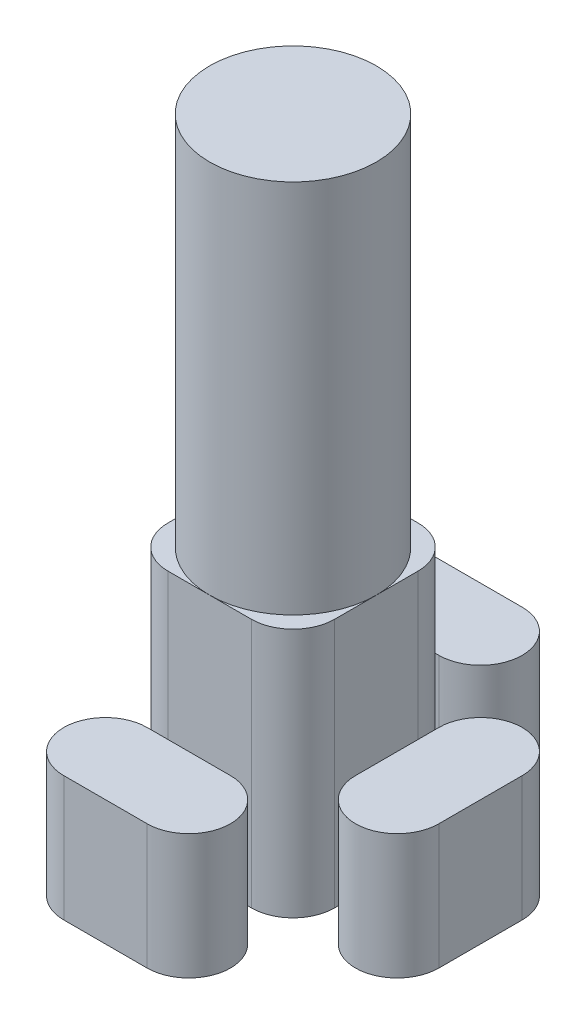
SolidWorks part; units mm, degrees
ref_plane "Front Plane" through (0, 0, 0) normal (0, 0, 1) x (1, 0, 0)
ref_plane "Top Plane" through (0, 0, 0) normal (0, 1, 0) x (1, 0, 0)
ref_plane "Right Plane" through (0, 0, 0) normal (1, 0, 0) x (0, 0, -1)
sketch "Sketch1" plane through (0, 0, 0) normal (0, 1, 0) x (1, 0, 0)
  line L0 (0, 0.2) -> (0, -0.2) construction
  line L1 (-0.1, -0.2) -> (0.1, -0.2)
  line L2 (-0.2, -0.1) -> (-0.2, 0.1)
  line L3 (-0.1, 0.2) -> (0.1, 0.2)
  line L4 (0.2, -0.1) -> (0.2, 0.1)
  line L5 (0.45, -0.1) -> (0.45, 0.1)
  line L6 (0.25, -0.1) -> (0.25, 0.1)
  line L11 (0.1, 0.25) -> (-0.1, 0.25)
  line L12 (0.1, 0.45) -> (-0.1, 0.45)
  line L13 (-0.2, 0) -> (0.2, 0) construction
  line L14 (0.1, -0.45) -> (-0.1, -0.45)
  line L15 (0.1, -0.25) -> (-0.1, -0.25)
  arc A1 (-0.2, 0.1) -> (-0.1, 0.2) centre (-0.1, 0.1) cw
  arc A2 (0.2, 0.1) -> (0.1, 0.2) centre (0.1, 0.1) ccw
  arc A3 (0.2, -0.1) -> (0.1, -0.2) centre (0.1, -0.1) cw
  arc A4 (-0.2, -0.1) -> (-0.1, -0.2) centre (-0.1, -0.1) ccw
  arc A5 (0.25, 0.1) -> (0.35, 0.2) centre (0.35, 0.1) cw
  arc A6 (0.45, 0.1) -> (0.35, 0.2) centre (0.35, 0.1) ccw
  arc A7 (0.45, -0.1) -> (0.35, -0.2) centre (0.35, -0.1) cw
  arc A8 (0.25, -0.1) -> (0.35, -0.2) centre (0.35, -0.1) ccw
  arc A17 (-0.1, 0.45) -> (-0.2, 0.35) centre (-0.1, 0.35) ccw
  arc A18 (0.1, 0.25) -> (0.2, 0.35) centre (0.1, 0.35) ccw
  arc A19 (0.1, 0.45) -> (0.2, 0.35) centre (0.1, 0.35) cw
  arc A20 (-0.1, 0.25) -> (-0.2, 0.35) centre (-0.1, 0.35) cw
  arc A21 (-0.1, -0.25) -> (-0.2, -0.35) centre (-0.1, -0.35) ccw
  arc A22 (0.1, -0.45) -> (0.2, -0.35) centre (0.1, -0.35) ccw
  arc A23 (0.1, -0.25) -> (0.2, -0.35) centre (0.1, -0.35) cw
  arc A24 (-0.1, -0.45) -> (-0.2, -0.35) centre (-0.1, -0.35) cw
  dimension "D1" = 0.05
  dimension "D2" = 2
extrude "Boss-Extrude1" add sketch "Sketch1" along normal blind 0.6
sketch "Sketch2" plane through (0, 0.6, 0) normal (0, 1, 0) x (1, 0, 0)
  line L0 (-0.1, -0.45) -> (0.1, -0.45) construction
  line L1 (0.1, -0.25) -> (-0.1, -0.25) construction
  line L2 (0.25, 0.1) -> (0.25, -0.1) construction
  line L3 (0.45, -0.1) -> (0.45, 0.1) construction
  line L4 (-0.1, 0.25) -> (0.1, 0.25) construction
  line L5 (0.1, 0.45) -> (-0.1, 0.45) construction
  line L6 (-0.1, -0.45) -> (0.1, -0.45)
  line L7 (0.1, -0.25) -> (-0.1, -0.25)
  line L8 (0.25, 0.1) -> (0.25, -0.1)
  line L9 (0.45, -0.1) -> (0.45, 0.1)
  line L10 (-0.1, 0.25) -> (0.1, 0.25)
  line L11 (0.1, 0.45) -> (-0.1, 0.45)
  arc A0 (-0.1, -0.25) -> (-0.1, -0.45) centre (-0.1, -0.35) ccw construction
  arc A1 (0.1, -0.45) -> (0.1, -0.25) centre (0.1, -0.35) ccw construction
  arc A2 (0.45, 0.1) -> (0.25, 0.1) centre (0.35, 0.1) ccw construction
  arc A3 (0.25, -0.1) -> (0.45, -0.1) centre (0.35, -0.1) ccw construction
  arc A4 (-0.1, 0.45) -> (-0.1, 0.25) centre (-0.1, 0.35) ccw construction
  arc A5 (0.1, 0.25) -> (0.1, 0.45) centre (0.1, 0.35) ccw construction
  arc A6 (-0.1, -0.25) -> (-0.1, -0.45) centre (-0.1, -0.35) ccw
  arc A7 (0.1, -0.45) -> (0.1, -0.25) centre (0.1, -0.35) ccw
  arc A8 (0.45, 0.1) -> (0.25, 0.1) centre (0.35, 0.1) ccw
  arc A9 (0.25, -0.1) -> (0.45, -0.1) centre (0.35, -0.1) ccw
  arc A10 (-0.1, 0.45) -> (-0.1, 0.25) centre (-0.1, 0.35) ccw
  arc A11 (0.1, 0.25) -> (0.1, 0.45) centre (0.1, 0.35) ccw
extrude "Cut-Extrude1" cut sketch "Sketch2" against normal blind 0.3
sketch "Sketch3" plane through (0, 0.6, 0) normal (0, 1, 0) x (1, 0, 0)
  circle A0 centre (0, 0) radius 0.2
extrude "Boss-Extrude2" add sketch "Sketch3" along normal blind 0.9
